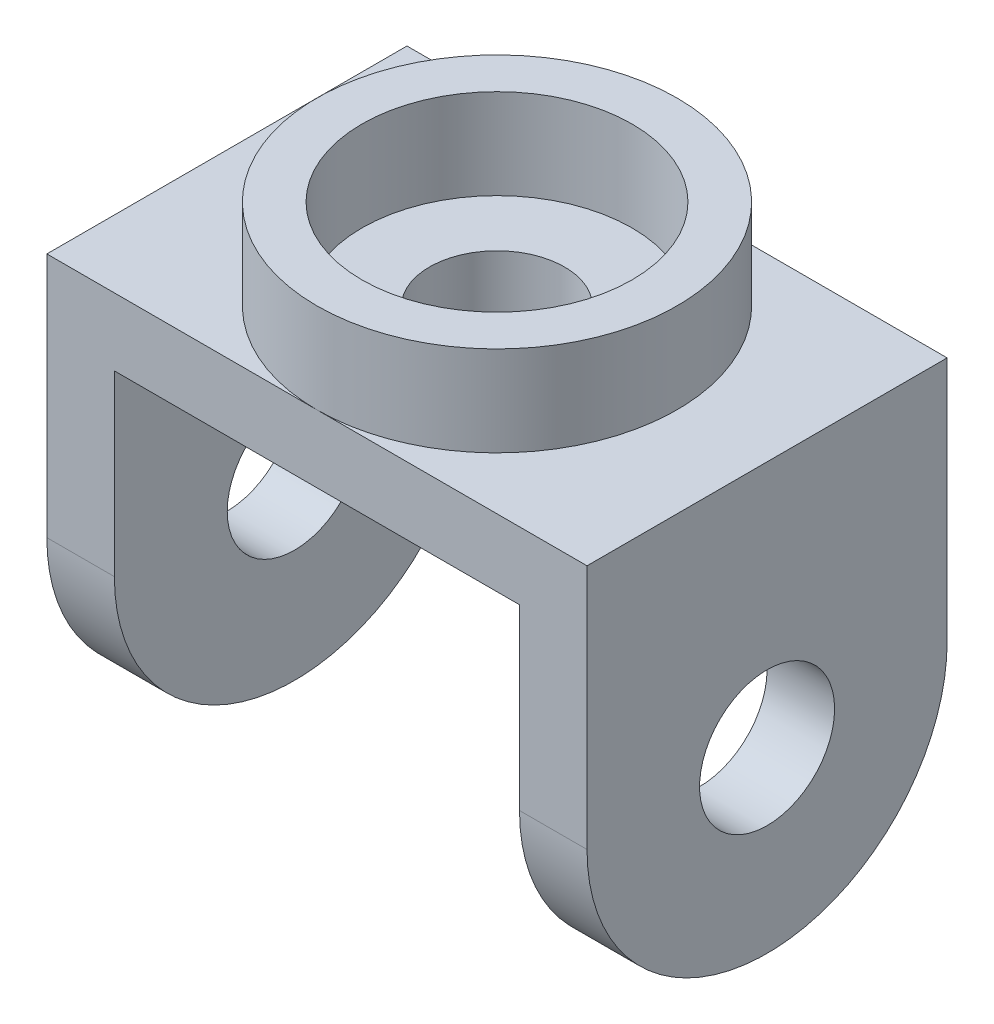
SolidWorks part; units mm, degrees
ref_plane "Front Plane" through (0, 0, 0) normal (0, 0, 1) x (1, 0, 0)
ref_plane "Top Plane" through (0, 0, 0) normal (0, 1, 0) x (1, 0, 0)
ref_plane "Right Plane" through (0, 0, 0) normal (1, 0, 0) x (0, 0, -1)
sketch "Sketch2" plane through (0, 0, 0) normal (0, 1, 0) x (1, 0, 0)
  line L0 (-15.24, 0) -> (15.24, 0) construction
  line L1 (-15.24, -10.16) -> (15.24, -10.16)
  line L2 (-15.24, -10.16) -> (-15.24, 10.16)
  line L3 (-15.24, 10.16) -> (15.24, 10.16)
  line L4 (15.24, -10.16) -> (15.24, 10.16)
  line L5 (-15.24, -10.16) -> (15.24, 10.16) construction
  line L6 (-15.24, 10.16) -> (15.24, -10.16) construction
  point P0 (0, 0)
  dimension "D1" = 20.32
  dimension "D2" = 30.48
extrude "Boss-Extrude1" add sketch "Sketch2" along normal blind 3.81
sketch "Sketch3" plane through (0, 3.81, 0) normal (0, 1, 0) x (1, 0, 0)
  circle A0 centre (0, 0) radius 10.16
  circle A1 centre (0, 0) radius 76.2
  circle A2 centre (0, 0) radius 7.62
  dimension "D1" = 15.24
  dimension "D2" = 20.32
extrude "Boss-Extrude2" add sketch "Sketch3" along normal blind 5.08 contours A0 A2
sketch "Sketch4" plane through (0, 3.81, 0) normal (0, 1, 0) x (1, 0, 0)
  circle A0 centre (0, 0) radius 3.81
  dimension "D1" = 7.62
extrude "Cut-Extrude1" cut sketch "Sketch4" against normal through all
sketch "Sketch6" plane through (15.24, 0, 0) normal (1, 0, 0) x (0, 0, -1)
  line L0 (-10.16, 3.81) -> (-10.16, -10.0548)
  line L1 (10.16, 3.81) -> (10.16, -10.0548)
  line L3 (-10.16, 3.81) -> (10.16, 3.81)
  arc A0 (-10.16, -10.0548) -> (10.16, -10.0548) centre (0, -10.0548) ccw
  dimension "D2" = 10.16
  dimension "D1" = 13.8648
extrude "Boss-Extrude3" add sketch "Sketch6" against normal blind 3.81
sketch "Sketch11" plane through (15.24, 0, 0) normal (1, 0, 0) x (0, 0, -1)
  line L0 (-10.16, 3.81) -> (10.16, 3.81) construction
  circle A0 centre (0, -10.16) radius 3.81
  dimension "D1" = 7.62
  dimension "D2" = 13.97
extrude "Cut-Extrude3" cut sketch "Sketch11" against normal blind 3.81
ref_plane "Plane4" through (-15.24, 0, 0) normal (-1, 0, 0) x (0, 0, 1)
sketch "Sketch12" plane through (-15.24, 0, 0) normal (-1, 0, 0) x (0, 0, 1)
  line L0 (-10.16, 3.81) -> (-10.16, -10.0548)
  line L1 (-10.16, 3.81) -> (10.16, 3.81)
  line L2 (10.16, 3.81) -> (10.16, -10.0548)
  arc A0 (-10.16, -10.0548) -> (10.16, -10.0548) centre (0, -10.0548) ccw
  circle A1 centre (0, -10.0548) radius 3.7918
extrude "Boss-Extrude5" add sketch "Sketch12" against normal blind 3.81
sketch "Sketch14" plane through (11.43, 0, 0) normal (-1, 0, 0) x (0, 0, 1)
  circle A0 centre (0, -10.16) radius 3.7929
